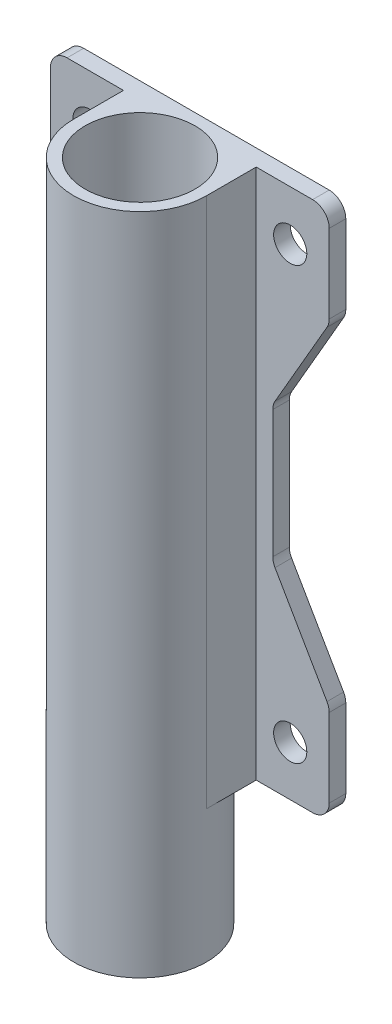
SolidWorks part; units mm, degrees
material "6061 Alloy"
ref_plane "Front" through (0, 0, 0) normal (0, 0, 1) x (1, 0, 0)
ref_plane "Top" through (0, 0, 0) normal (0, 1, 0) x (1, 0, 0)
ref_plane "Right" through (0, 0, 0) normal (1, 0, 0) x (0, 0, -1)
sketch "Sketch2" plane through (0, 0, 0) normal (0, 0, 1) x (1, 0, 0)
  line L0 (0, 0) -> (-53.34, 0) construction
  line L1 (-53.34, -101.6) -> (53.34, -101.6)
  line L2 (-53.34, -101.6) -> (-53.34, -63.5)
  line L3 (-53.34, 101.6) -> (53.34, 101.6)
  line L4 (53.34, -101.6) -> (53.34, -63.5)
  line L5 (-53.34, -101.6) -> (53.34, 101.6) construction
  line L6 (-53.34, 101.6) -> (53.34, -101.6) construction
  line L7 (0, 0) -> (0, 101.6) construction
  line L8 (-53.34, 63.5) -> (-31.75, 26.105)
  line L9 (-31.75, 26.105) -> (-31.75, -26.105)
  line L10 (-53.34, -63.5) -> (-31.75, -26.105)
  line L11 (53.34, -63.5) -> (31.75, -26.105)
  line L12 (31.75, 26.105) -> (31.75, -26.105)
  line L13 (53.34, 63.5) -> (31.75, 26.105)
  line L14 (-53.34, 63.5) -> (-53.34, 101.6)
  line L15 (-53.34, 0) -> (-53.34, 63.5) construction
  line L16 (-53.34, -63.5) -> (-53.34, 0) construction
  line L17 (53.34, 63.5) -> (53.34, 101.6)
  line L18 (53.34, -63.5) -> (53.34, 63.5) construction
  circle A0 centre (-38.4175, 82.55) radius 6.35
  circle A1 centre (-38.4175, -82.55) radius 6.35
  circle A2 centre (38.4175, -82.55) radius 6.35
  circle A3 centre (38.4175, 82.55) radius 6.35
  point P0 (0, 0)
  point P13 (-31.75, 0)
  dimension "D6" = 12.7
  dimension "D1" = 203.2
  dimension "D2" = 106.68
  dimension "D3" = 30
  dimension "D4" = 38.1
  dimension "D5" = 63.5
  dimension "D7" = 14.9225
  dimension "D8" = 19.05
extrude "Boss-Extrude1" add sketch "Sketch2" along normal blind 6.35
sketch "Sketch3" plane through (0, -101.6, 0) normal (0, -1, 0) x (1, 0, 0)
  line L3 (-53.34, 0) -> (53.34, 0) construction
  line L4 (-25.4, 25.4) -> (-25.4, 6.35)
  line L5 (-53.34, 6.35) -> (53.34, 6.35) construction
  line L6 (-25.4, 6.35) -> (-16.8005, 6.35)
  line L7 (25.4, 25.4) -> (25.4, 6.35)
  line L8 (25.4, 6.35) -> (16.8005, 6.35)
  arc A1 (-16.8005, 6.35) -> (16.8005, 6.35) centre (0, 25.4) ccw
  arc A2 (25.4, 25.4) -> (-25.4, 25.4) centre (0, 25.4) ccw
  arc A3 (25.4, 25.4) -> (-25.4, 25.4) centre (0, 25.4) ccw
  arc A4 (-16.8005, 6.35) -> (16.8005, 6.35) centre (0, 25.4) ccw
  point P2 (0, 50.8)
  line M5 (53.34, 6.35) -> (-53.34, 6.35)
  dimension "D1" = 50.8
extrude "Boss-Extrude7" add sketch "Sketch3" against normal up to surface (203.2 mm away) contours A1 M5 | A2 M5 up to face at (0, 101.6, 3.175)
sketch "Sketch4" plane through (0, -101.6, 0) normal (0, -1, 0) x (1, 0, 0)
  circle A2 centre (0, 25.4) radius 25.4
  arc A3 (25.4, 25.4) -> (-25.4, 25.4) centre (0, 25.4) ccw construction
extrude "Boss-Extrude8" add sketch "Sketch4" along normal blind 50.8
sketch "Sketch5" plane through (0, -152.4, 0) normal (0, -1, 0) x (1, 0, 0)
  circle A0 centre (0, 25.4) radius 21.0287
  circle A1 centre (0, 25.4) radius 25.4 construction
  dimension "D1" = 42.0573
extrude "Cut-Extrude2" cut sketch "Sketch5" against normal through all
fillet "Fillet1" radius 6.35 12 edges at (53.34, 63.5, 3.175) (31.75, 26.105, 3.175) (31.75, -26.105, 3.175) (53.34, -63.5, 3.175) (53.34, -101.6, 3.175) (-53.34, -101.6, 3.175) (-53.34, -63.5, 3.175) (-31.75, -26.105, 3.175) (-31.75, 26.105, 3.175) (-53.34, 63.5, 3.175) (-53.34, 101.6, 3.175) (53.34, 101.6, 3.175)
equation "\"ID\"= 1.6558in"
equation "\"Overall_Length\"= 10in"
equation "\"Overhang\"= 2in"
equation "\"D1@Boss-Extrude7\"=\"Overhang\""
equation "\"D1@Boss-Extrude8\"=\"Overhang\""
equation "\"D1@Sketch5\"=\"ID\""
equation "\"D1@Sketch2\"=\"Overall_Length\"-\"Overhang\""
